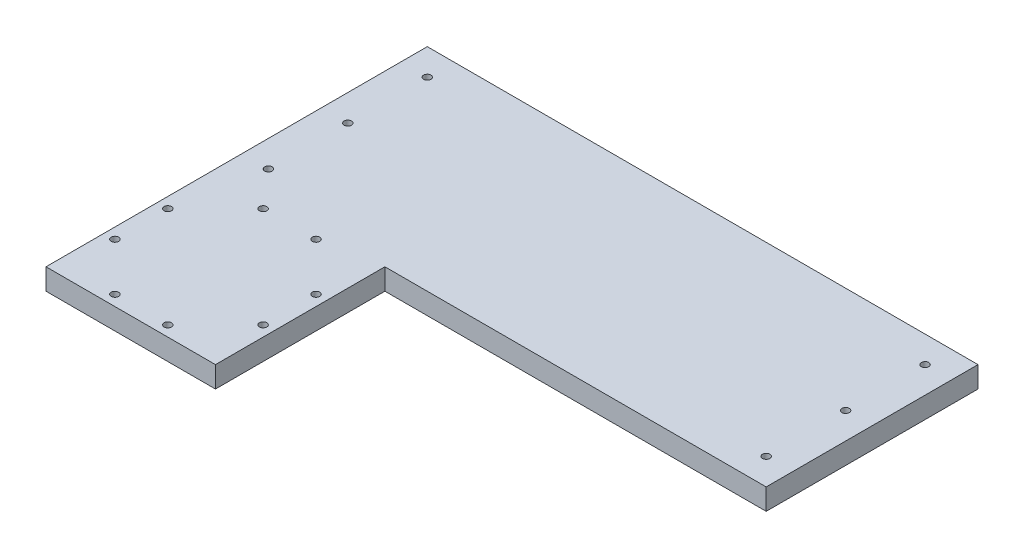
SolidWorks part; units mm, degrees
ref_plane "Front Plane" through (0, 0, 0) normal (0, 0, 1) x (1, 0, 0)
ref_plane "Top Plane" through (0, 0, 0) normal (0, 1, 0) x (1, 0, 0)
ref_plane "Right Plane" through (0, 0, 0) normal (1, 0, 0) x (0, 0, -1)
sketch "Sketch1" plane through (0, 0, 0) normal (0, 1, 0) x (1, 0, 0)
  line L1 (-260, 100) -> (260, 100)
  line L2 (-260, 100) -> (-260, -100)
  line L3 (-260, -100) -> (260, -100)
  line L4 (260, 100) -> (260, -100)
  line L5 (-260, 100) -> (260, -100) construction
  line L6 (-260, -100) -> (260, 100) construction
  point P0 (0, 0)
  dimension "D1" = 520
  dimension "D2" = 200
extrude "Boss-Extrude1" add sketch "Sketch1" along normal blind 20
sketch "Sketch6" plane through (0, 0, 0) normal (0, -1, 0) x (1, 0, 0)
  line L1 (-260, 100) -> (-100, 100)
  line L2 (-260, 100) -> (-260, 260)
  line L3 (-260, 260) -> (-100, 260)
  line L4 (-100, 100) -> (-100, 260)
  point P5 (0, 0)
  point P7 (0, 0)
  dimension "D1" = 160
  dimension "D2" = 160
extrude "Boss-Extrude2" add sketch "Sketch6" against normal up to surface (20 mm away) up to face at (0, 20, 0)
hole_wizard "CBORE for M6 SHCS1" positions "Sketch4" profile "Sketch5" counterbore size "M6" standard "ANSI Metric" end condition up to next
sketch "Sketch4" plane through (0, 0, 0) normal (0, -1, 0) x (-1, 0, 0)
  line L0 (-235, 75) -> (-235, -75) construction
  line L2 (-235, -75) -> (235, -75) construction
  line L4 (235, 75) -> (235, -75) construction
  line L6 (-260, -100) -> (-260, 100) construction
  line L7 (205, -110) -> (155, -110) construction
  line L13 (205, -250) -> (155, -250) construction
  line L15 (100, -260) -> (260, -260) construction
  line L18 (100, -100) -> (-260, -100) construction
  line L19 (250, -155) -> (250, -205) construction
  line L21 (110, -155) -> (110, -205) construction
  line L23 (260, -260) -> (260, 100) construction
  line L25 (100, -100) -> (100, -260) construction
  point P0 (-235, 75)
  point P2 (-235, -75)
  point P4 (235, 75)
  point P6 (235, -75)
  point P20 (0, -75)
  point P24 (-235, 0)
  point P30 (235, 0)
  point P43 (155, -250)
  point P45 (205, -250)
  point P47 (155, -110)
  point P49 (205, -110)
  point P67 (180, -110)
  point P68 (180, -250)
  point P73 (180, -260)
  point P92 (250, -180)
  point P96 (110, -180)
  point P101 (110, -155)
  point P104 (250, -155)
  point P107 (250, -205)
  point P110 (110, -205)
  point P114 (100, -180)
  dimension "D1" = 150
  dimension "D2" = 25
  dimension "D3" = 50
  dimension "D4" = 10
  dimension "D5" = 10
  dimension "D6" = 10
  dimension "D7" = 10
sketch "Sketch5" plane through (235, 0, -75) normal (1, 0, 0) x (0, 0, -1)
  line L0 (0, 0) -> (0, 20)
  line L1 (0, 20) -> (3.5, 20)
  line L3 (3.5, 20) -> (3.5, 6)
  line L4 (5.5, 6) -> (3.5, 6)
  line L5 (5.5, 6) -> (5.5, 0.021)
  line L6 (5.5, 0.021) -> (5.525, 0)
  line L7 (5.525, 0) -> (0, 0)
  line L8 (-5.5, 0.021) -> (-5.525, 0) construction
  line L11 (0, -6.35) -> (0, 107.95) construction
  dimension "Thru Hole Dia." = 7
  dimension "Thru Hole Depth" = 20
  dimension "C'Bore Dia." = 11
  dimension "C'Bore Depth" = 6
  dimension "Near C'Sink Dia." = 11.05
  dimension "Near C'Sink Angle" = 100
